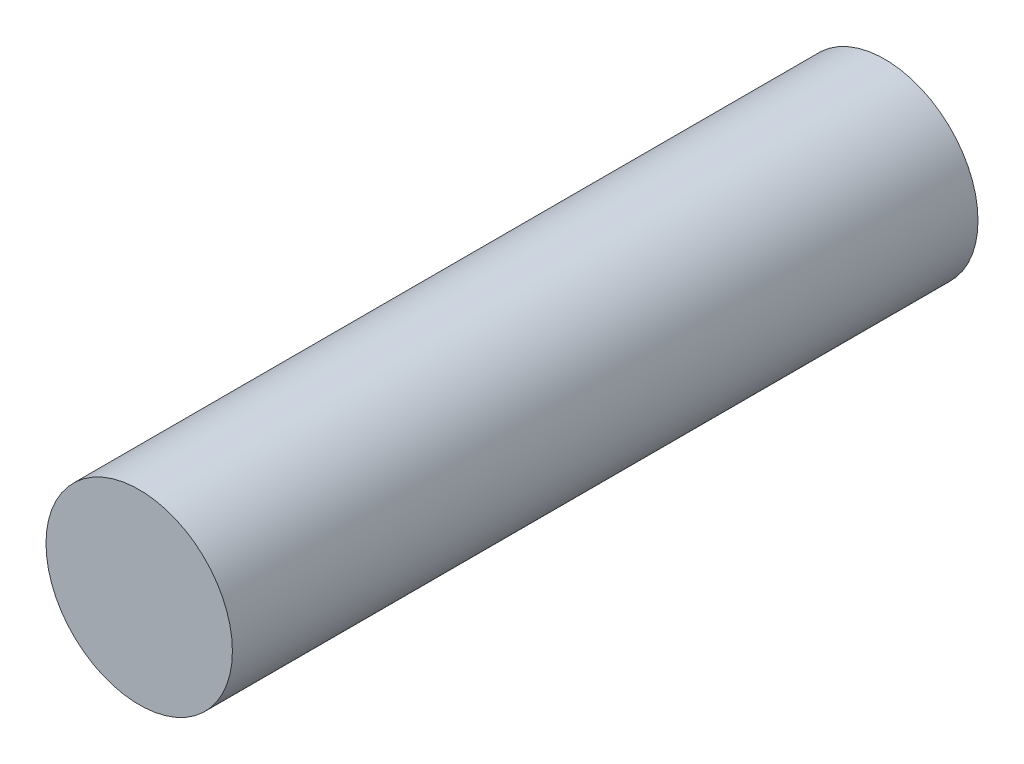
SolidWorks part; units mm, degrees
ref_plane "Front Plane" through (0, 0, 0) normal (0, 0, 1) x (1, 0, 0)
ref_plane "Top Plane" through (0, 0, 0) normal (0, 1, 0) x (1, 0, 0)
ref_plane "Right Plane" through (0, 0, 0) normal (1, 0, 0) x (0, 0, -1)
sketch "Sketch1" plane through (0, 0, 0) normal (0, 0, 1) x (1, 0, 0)
  circle A0 centre (0, 0) radius 38.1
  dimension "D1" = 76.2
extrude "Boss-Extrude1" add sketch "Sketch1" along normal mid plane 304.8
